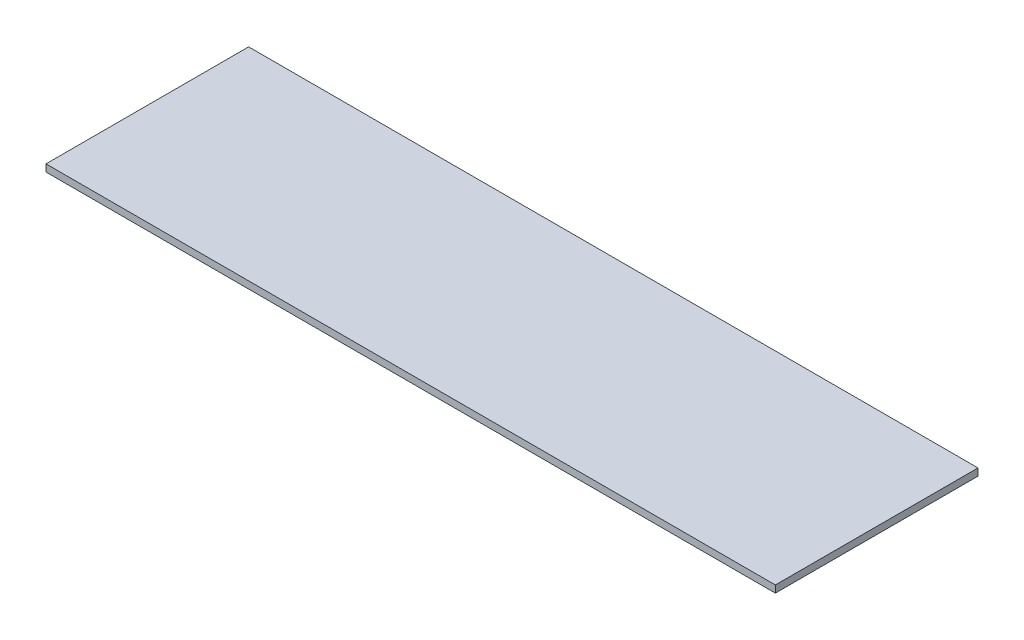
SolidWorks part; units mm, degrees
material "PLA"
ref_plane "Front Plane" through (0, 0, 0) normal (0, 0, 1) x (1, 0, 0)
ref_plane "Top Plane" through (0, 0, 0) normal (0, 1, 0) x (1, 0, 0)
ref_plane "Right Plane" through (0, 0, 0) normal (1, 0, 0) x (0, 0, -1)
sketch "Sketch1" plane through (0, 0, 0) normal (0, 1, 0) x (1, 0, 0)
  line L1 (-425.7288, 49.811) -> (87.0712, 49.811)
  line L2 (-425.7288, 49.811) -> (-425.7288, -92.669)
  line L3 (-425.7288, -92.669) -> (87.0712, -92.669)
  line L4 (87.0712, 49.811) -> (87.0712, -92.669)
  dimension "D1" = 512.8
  dimension "D2" = 142.48
extrude "Boss-Extrude1" add sketch "Sketch1" along normal blind 5 contours L2 L3 L4 L1
